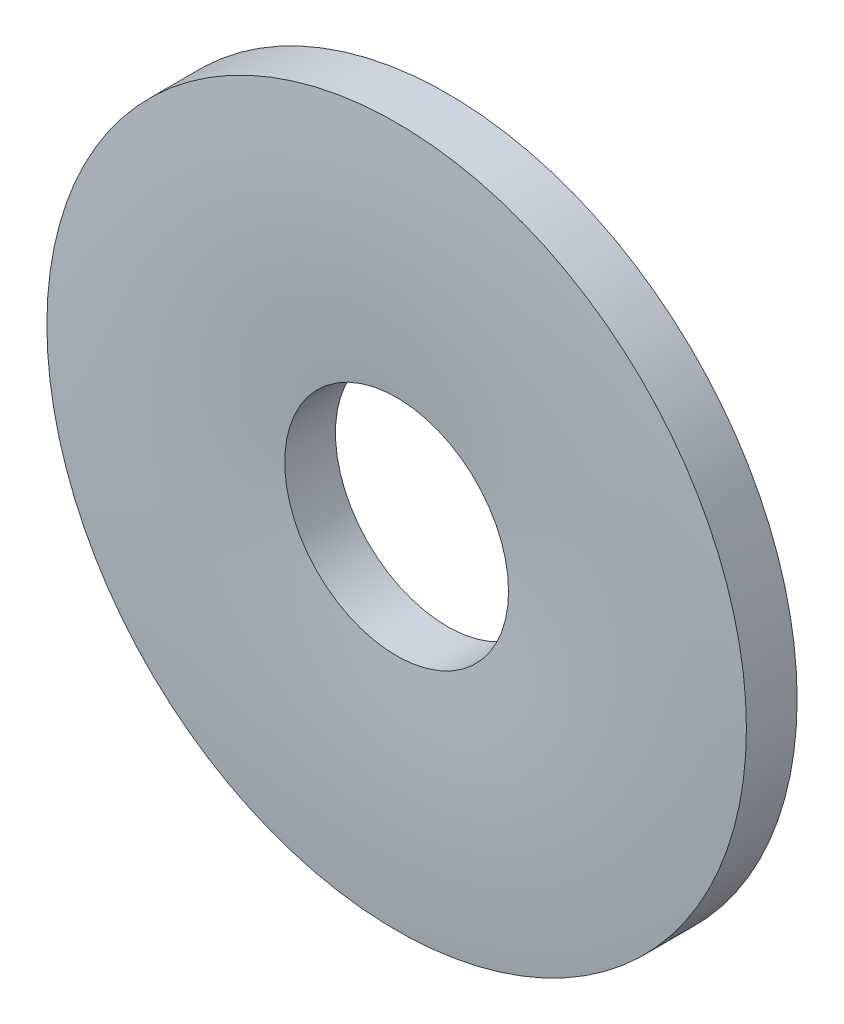
SolidWorks part; units mm, degrees
ref_plane "Front Plane" through (0, 0, 0) normal (0, 0, 1) x (1, 0, 0)
ref_plane "Top Plane" through (0, 0, 0) normal (0, 1, 0) x (1, 0, 0)
ref_plane "Right Plane" through (0, 0, 0) normal (1, 0, 0) x (0, 0, -1)
sketch "Sketch1" plane through (0, 0, 0) normal (0, 0, 1) x (1, 0, 0)
  circle A0 centre (0, 0) radius 3.2
  circle A1 centre (0, 0) radius 10
  dimension "ID" = 6.4
  dimension "OD" = 20
sketch "Sketch2" plane through (0, 0, 0) normal (1, 0, 0) x (0, 0, -1)
  line L0 (-0.8, 10) -> (0.8, 10) construction
  line L1 (-0.8, 0) -> (0.8, 0) construction
  point P2 (0, 10)
  dimension "Thickness Range" = 1.6
sketch "Sketch3" plane through (0, 0, 0) normal (1, 0, 0) x (0, 0, -1)
  line L0 (0.8, 10) -> (-0.6501, 10)
  line L1 (0.8, 3.2) -> (-0.6501, 3.2)
  line L2 (0.8, 3.2) -> (0.8, 10)
  line L3 (-0.8, 10) -> (-0.8, 3.2) construction
  arc A0 (-0.6501, 3.2) -> (-0.6501, 10) centre (37.8289, 6.6) cw
  point P9 (0, 3.2)
  dimension "D1" = 0.1499
revolve "Revolve1" add sketch "Sketch3" angle 360 about L1
equation "\"D1@Sketch3\"=\"Thickness Range@Sketch2\"*.0937"
